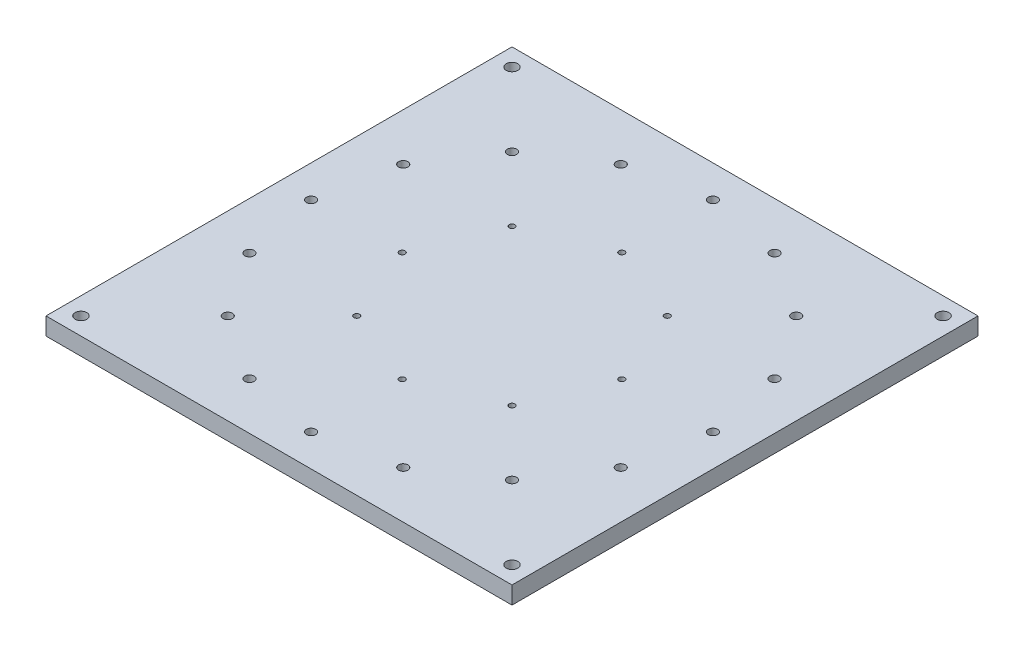
SolidWorks part; units mm, degrees
material "Wrought Stainless Steel"
ref_plane "Front Plane" through (0, 0, 0) normal (0, 0, 1) x (1, 0, 0)
ref_plane "Top Plane" through (0, 0, 0) normal (0, 1, 0) x (1, 0, 0)
ref_plane "Right Plane" through (0, 0, 0) normal (1, 0, 0) x (0, 0, -1)
sketch "Sketch1" plane through (0, 0, 0) normal (0, 1, 0) x (1, 0, 0)
  line L1 (-400, 400) -> (400, 400)
  line L2 (-400, 400) -> (-400, -400)
  line L3 (-400, -400) -> (400, -400)
  line L4 (400, 400) -> (400, -400)
  line L5 (-400, 400) -> (400, -400) construction
  line L6 (-400, -400) -> (400, 400) construction
  point P0 (0, 0)
  dimension "D1" = 800
  dimension "D2" = 800
extrude "Boss-Extrude1" add sketch "Sketch1" along normal mid plane 30
sketch "Sketch2" plane through (0, 15, 0) normal (0, 1, 0) x (1, 0, 0)
  line L0 (0, -1000) -> (0, 49000) construction
  line L1 (-1000, 0) -> (49000, 0) construction
  line L2 (0, 0) -> (133.2896, 133.2896) construction
  line L3 (-707.1068, 707.1068) -> (34648.2323, -34648.2323) construction
  circle A0 centre (0, 0) radius 188.5 construction
  circle A1 centre (0, 188.5) radius 5
  circle A2 centre (188.5, 0) radius 5
  circle A3 centre (0, -188.5) radius 5
  circle A4 centre (-188.5, 0) radius 5
  circle A5 centre (133.2896, 133.2896) radius 5
  circle A6 centre (-133.2896, -133.2896) radius 5
  circle A7 centre (133.2896, -133.2896) radius 5
  circle A8 centre (-133.2896, 133.2896) radius 5
  dimension "D1" = 377
  dimension "D2" = 10
  dimension "D3" = 10
  dimension "D5" = 10
  dimension "D4" = 45
extrude "Cut-Extrude1" cut sketch "Sketch2" against normal blind 15
sketch "Sketch4" plane through (0, 15, 0) normal (0, 1, 0) x (1, 0, 0)
  line L0 (-1000, 0) -> (49000, 0) construction
  line L1 (0, -1000) -> (0, 49000) construction
  circle A0 centre (0, 0) radius 345 construction
  circle A1 centre (0, 345) radius 8
  circle A2 centre (132.0258, 318.7384) radius 8
  circle A3 centre (243.9518, 243.9518) radius 8
  circle A4 centre (318.7384, 132.0258) radius 8
  circle A5 centre (345, 0) radius 8
  circle A6 centre (318.7384, -132.0258) radius 8
  circle A7 centre (243.9518, -243.9518) radius 8
  circle A8 centre (132.0258, -318.7384) radius 8
  circle A9 centre (0, -345) radius 8
  circle A10 centre (-132.0258, -318.7384) radius 8
  circle A11 centre (-243.9518, -243.9518) radius 8
  circle A12 centre (-318.7384, -132.0258) radius 8
  circle A13 centre (-345, 0) radius 8
  circle A14 centre (-318.7384, 132.0258) radius 8
  circle A15 centre (-243.9518, 243.9518) radius 8
  circle A16 centre (-132.0258, 318.7384) radius 8
  point P42 (0, 0)
  dimension "D1" = 690
  dimension "D2" = 16
  dimension "D3" = 16
extrude "Cut-Extrude2" cut sketch "Sketch4" against normal blind 15
sketch "Sketch5" plane through (0, 15, 0) normal (0, 1, 0) x (1, 0, 0)
  line L0 (400, 400) -> (-400, 400) construction
  line L1 (-400, 400) -> (-400, -400) construction
  line L2 (-1000, 0) -> (49000, 0) construction
  line L3 (0, -1000) -> (0, 49000) construction
  circle A0 centre (-370, 370) radius 10
  circle A1 centre (370, 370) radius 10
  circle A2 centre (370, -370) radius 10
  circle A3 centre (-370, -370) radius 10
  dimension "D1" = 20
  dimension "D2" = 30
  dimension "D3" = 30
extrude "Cut-Extrude3" cut sketch "Sketch5" against normal through all
